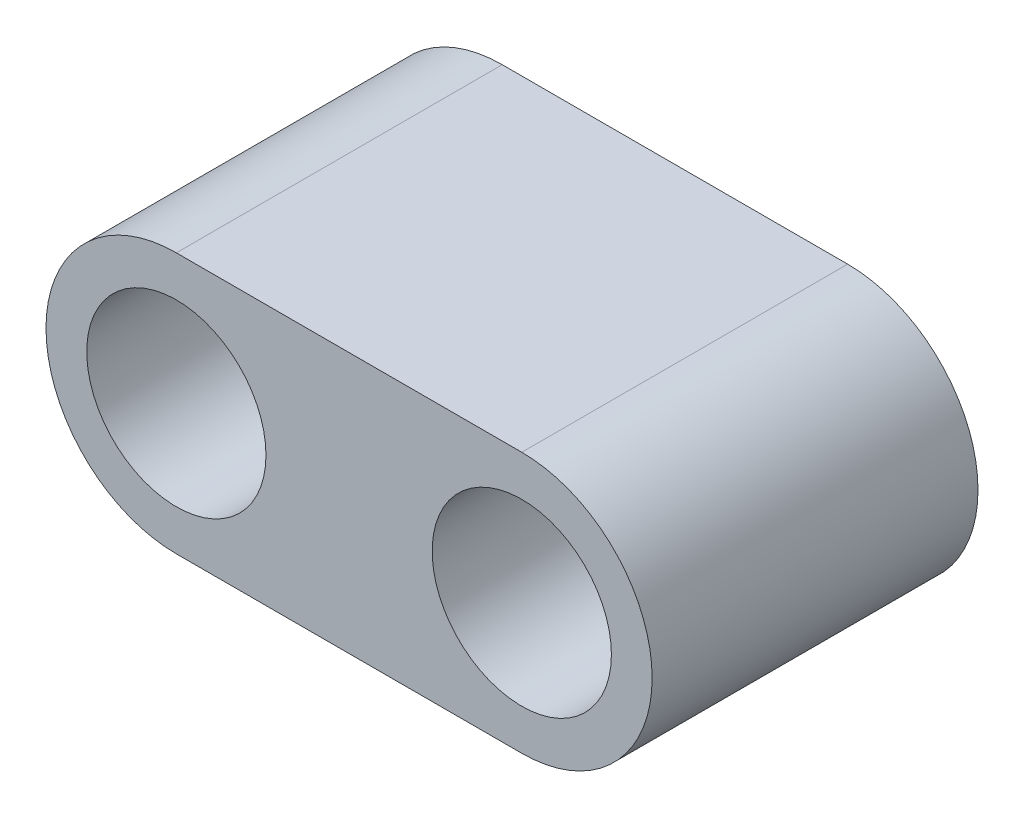
SolidWorks part; units mm, degrees
ref_plane "Front Plane" through (0, 0, 0) normal (0, 0, 1) x (1, 0, 0)
ref_plane "Top Plane" through (0, 0, 0) normal (0, 1, 0) x (1, 0, 0)
ref_plane "Right Plane" through (0, 0, 0) normal (1, 0, 0) x (0, 0, -1)
sketch "Sketch1" plane through (0, 0, 0) normal (0, 0, 1) x (1, 0, 0)
  line L0 (0, 0) -> (26.5, 0)
  line L1 (0, -20) -> (26.5, -20)
  arc A1 (0, 0) -> (0, -20) centre (0, -10) ccw
  arc A2 (26.5, 0) -> (26.5, -20) centre (26.5, -10) cw
  dimension "D1" = 10
  dimension "D2" = 26.5
extrude "Boss-Extrude1" add sketch "Sketch1" along normal blind 25
sketch "Sketch2" plane through (0, 0, 25) normal (0, 0, 1) x (1, 0, 0)
  line L0 (0, 0) -> (0, -20) construction
  line L1 (26.5, 0) -> (26.5, -20) construction
  line L2 (26.5, -10) -> (0, -10) construction
  circle A0 centre (0, -10) radius 6.875
  circle A1 centre (26.5, -10) radius 6.875
  dimension "D1" = 13.75
extrude "Cut-Extrude1" cut sketch "Sketch2" against normal through all
